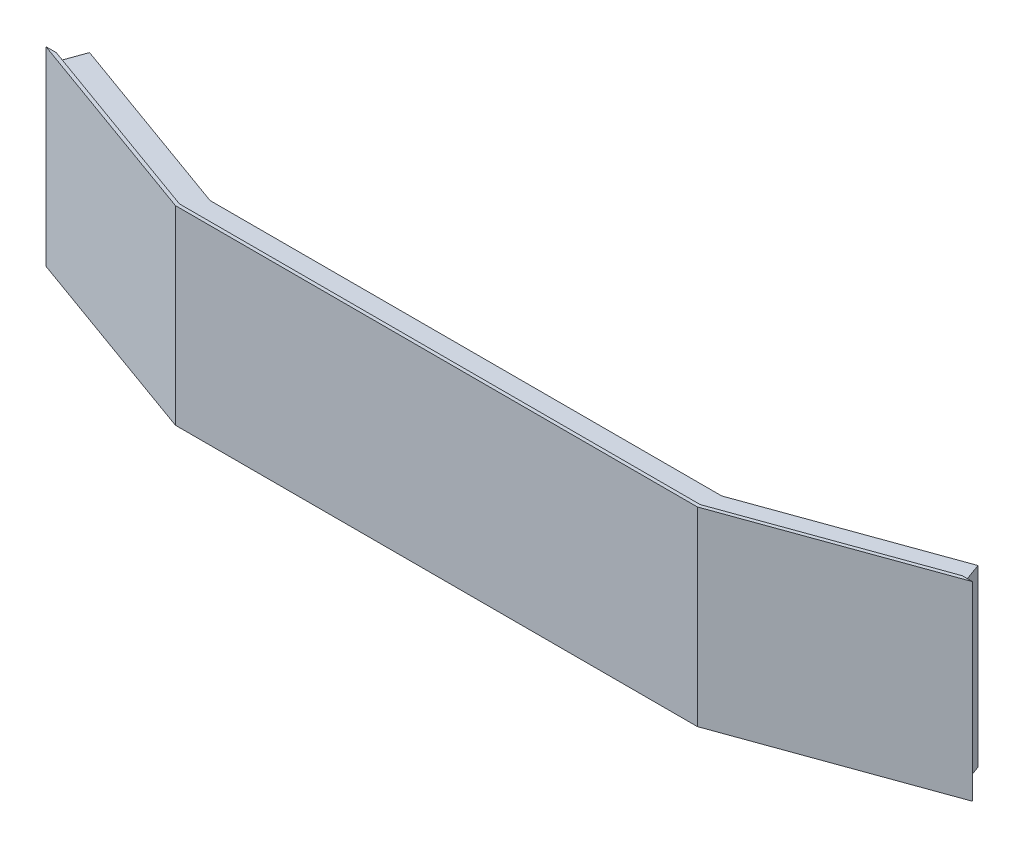
SolidWorks part; units mm, degrees
ref_plane "Front Plane" through (0, 0, 0) normal (0, 0, 1) x (1, 0, 0)
ref_plane "Top Plane" through (0, 0, 0) normal (0, 1, 0) x (1, 0, 0)
ref_plane "Right Plane" through (0, 0, 0) normal (1, 0, 0) x (0, 0, -1)
sketch "Sketch1" plane through (0, 0, 0) normal (0, 1, 0) x (1, 0, 0)
  line L0 (-261, -120) -> (-150, -160)
  line L1 (-150, -160) -> (150, -160)
  line L2 (150, -160) -> (261, -120)
  line L3 (261, -120) -> (-261, -120) construction
  line L5 (-150.3494, -162) -> (150.3494, -162)
  line L8 (-257.4765, -120) -> (-261, -120)
  line L9 (-261, -120) -> (-266.8994, -120)
  line L10 (261, -120) -> (266.8994, -120)
  line L11 (-272.4494, -118) -> (-150.3494, -162) construction
  line L12 (266.8994, -120) -> (150.3494, -162)
  line L13 (150.3494, -162) -> (272.4494, -118) construction
  line L14 (272.4494, -118) -> (-272.4494, -118) construction
  line L15 (-150.3494, -162) -> (-266.8994, -120)
  dimension "D1" = 2
extrude "Boss-Extrude1" add sketch "Sketch1" along normal blind 109.6 contours L0 L1 L2 L10 L12 L5 L15 L9
ref_plane "Plane1" through (0, 4.5, 0) normal (0, 1, 0) x (1, 0, 0)
ref_plane "Plane2" through (0, 105.1, 0) normal (0, 1, 0) x (1, 0, 0)
sketch "Sketch2" plane through (0, 4.5, 0) normal (0, 1, 0) x (1, 0, 0)
  line L9 (147.3798, -145) -> (255.9147, -105.8883)
  line L10 (-147.3798, -145) -> (147.3798, -145)
  line L11 (-255.9147, -105.8883) -> (-147.3798, -145)
  line L12 (147.3798, -145) -> (255.9147, -105.8883)
  line L13 (-147.3798, -145) -> (147.3798, -145)
  line L14 (-255.9147, -105.8883) -> (-147.3798, -145)
  line L18 (-255.9147, -105.8883) -> (-261, -120)
  line L19 (255.9147, -105.8883) -> (261, -120)
  line L21 (150, -160) -> (261, -120)
  line L22 (-150, -160) -> (150, -160)
  line L23 (-261, -120) -> (-150, -160)
  line L24 (150, -160) -> (261, -120)
  line L25 (-150, -160) -> (150, -160)
  line L26 (-261, -120) -> (-150, -160)
  dimension "D1" = 15
  dimension "D2" = 0
sketch "Sketch4" plane through (0, 105.1, 0) normal (0, 1, 0) x (1, 0, 0)
  line L3 (-255.9147, -105.8883) -> (-147.3798, -145)
  line L4 (-147.3798, -145) -> (147.3798, -145)
  line L5 (147.3798, -145) -> (255.9147, -105.8883)
  line L9 (150, -160) -> (261, -120)
  line L10 (-150, -160) -> (150, -160)
  line L11 (-261, -120) -> (-150, -160)
  line L12 (150, -160) -> (261, -120)
  line L13 (-150, -160) -> (150, -160)
  line L14 (-261, -120) -> (-150, -160)
  line L19 (-261, -120) -> (-255.9147, -105.8883)
  line L22 (255.9147, -105.8883) -> (261, -120)
  dimension "D1" = 0
  dimension "D2" = 15
extrude "Boss-Extrude2" add sketch "Sketch2" along normal blind 2.54
extrude "Boss-Extrude3" add sketch "Sketch4" against normal blind 2.54
ref_plane "Plane3" through (-118.4369, 0, -20.6888) normal (0.9851, 0, 0.1721) x (0.1721, 0, -0.9851)
sketch "Sketch5" plane through (-118.4369, 0, -20.6888) normal (0.9851, 0, 0.1721) x (0.1721, 0, -0.9851)
  line L0 (-168.1977, 102.56) -> (-183.4249, 54.8)
  line L1 (-183.4249, 102.56) -> (-183.4249, 7.04) construction
  line L2 (-183.4249, 54.8) -> (-168.1977, 7.04) construction
rib "Rib2" sketch "Sketch5" sketch "Sketch5" thickness 2.54 extrusion direction parallel to sketch draft on no parameters "D1"=2.54
sketch "Sketch6" plane through (-118.4369, 0, -20.6888) normal (0.9851, 0, 0.1721) x (0.1721, 0, -0.9851)
  line L0 (-183.4249, 54.8) -> (-168.1977, 7.04)
rib "Rib3" sketch "Sketch6" sketch "Sketch6" thickness 2.54 extrusion direction parallel to sketch draft on no parameters "D1"=2.54
ref_plane "Plane4" through (118.4369, 0, -20.6888) normal (0.9851, 0, -0.1721) x (-0.1721, 0, -0.9851)
sketch "Sketch7" plane through (118.4369, 0, -20.6888) normal (0.9851, 0, -0.1721) x (-0.1721, 0, -0.9851)
  line L0 (-168.1977, 102.56) -> (-183.4249, 54.8)
  line L1 (-183.4249, 102.56) -> (-183.4249, 7.04) construction
  line L2 (-183.4249, 54.8) -> (-168.1977, 7.04) construction
rib "Rib4" sketch "Sketch7" sketch "Sketch7" thickness 2.54 extrusion direction parallel to sketch draft on no parameters "D1"=2.54
sketch "Sketch8" plane through (118.4369, 0, -20.6888) normal (0.9851, 0, -0.1721) x (-0.1721, 0, -0.9851)
  line L0 (-183.4249, 54.8) -> (-168.1977, 7.04)
rib "Rib5" sketch "Sketch8" sketch "Sketch8" thickness 2.54 extrusion direction parallel to sketch draft on no parameters "D1"=2.54
sketch "Sketch10" plane through (0, 0, 145) normal (0, 0, -1) x (-1, 0, 0)
  line L0 (0, 102.56) -> (0, 105.1) construction
  line L1 (-147.3798, 102.56) -> (147.3798, 102.56) construction
  line L2 (-147.3798, 105.1) -> (147.3798, 105.1) construction
  line L3 (0, 105.1) -> (0, 7.04) construction
  line L4 (-147.3798, 7.04) -> (147.3798, 7.04) construction
sketch "Sketch12" plane through (0, 0, 160) normal (0, 0, -1) x (-1, 0, 0)
  line L0 (0, 102.56) -> (0, 7.04) construction
sketch "Sketch13" plane through (0, 0, 0) normal (1, 0, 0) x (0, 0, -1)
  line L0 (-145, 102.56) -> (-160, 54.8)
  line L1 (-160, 102.56) -> (-160, 7.04) construction
  line L2 (-160, 54.8) -> (-145, 7.04) construction
rib "Rib6" sketch "Sketch13" sketch "Sketch13" thickness 2.54 extrusion direction parallel to sketch draft on no parameters "D1"=2.54
sketch "Sketch14" plane through (0, 0, 0) normal (1, 0, 0) x (0, 0, -1)
  line L0 (-160, 54.8) -> (-145, 7.04)
  line L1 (-160, 102.56) -> (-160, 7.04) construction
rib "Rib7" sketch "Sketch14" sketch "Sketch14" thickness 2.54 extrusion direction parallel to sketch draft on no parameters "D1"=2.54
sketch "Sketch15" plane through (68.271, 0, 189.4519) normal (-0.339, 0, -0.9408) x (-0.9408, 0, 0.339)
  line L0 (-204.8611, 7.04) -> (-89.494, 7.04) construction
  line L1 (-204.8611, 102.56) -> (-202.3211, 102.56)
  line L2 (-204.8611, 102.56) -> (-204.8611, 7.04)
  line L3 (-204.8611, 7.04) -> (-202.3211, 7.04)
  line L4 (-202.3211, 102.56) -> (-202.3211, 7.04)
  dimension "D1" = 2.54
extrude "Boss-Extrude4" add sketch "Sketch15" along normal blind 15
sketch "Sketch16" plane through (-68.271, 0, 189.4519) normal (0.339, 0, -0.9408) x (-0.9408, 0, -0.339)
  line L0 (204.8611, 7.04) -> (88.163, 7.04) construction
  line L1 (204.8611, 102.56) -> (202.3211, 102.56)
  line L2 (204.8611, 102.56) -> (204.8611, 7.04)
  line L3 (204.8611, 7.04) -> (202.3211, 7.04)
  line L4 (202.3211, 102.56) -> (202.3211, 7.04)
  dimension "D1" = 2.54
extrude "Boss-Extrude5" add sketch "Sketch16" along normal blind 15
equation "\"gap\"= 1mm"
equation "\"casewidth\"= 2mm"
